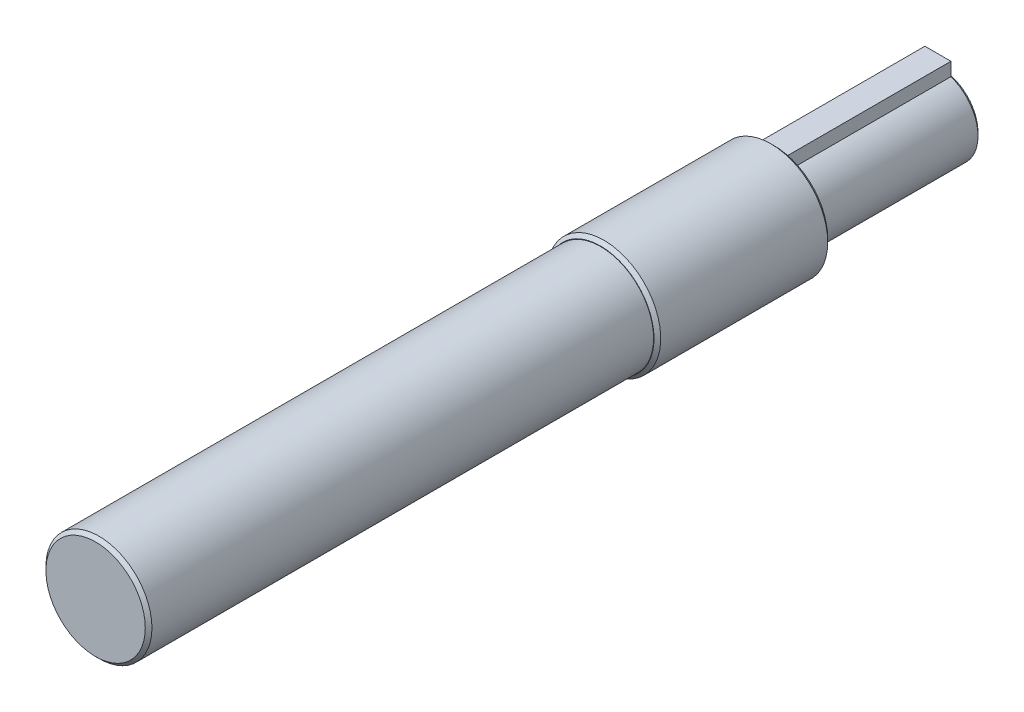
SolidWorks part; units mm, degrees
ref_plane "Front Plane" through (0, 0, 0) normal (0, 0, 1) x (1, 0, 0)
ref_plane "Top Plane" through (0, 0, 0) normal (0, 1, 0) x (1, 0, 0)
ref_plane "Right Plane" through (0, 0, 0) normal (1, 0, 0) x (0, 0, -1)
sketch "Sketch2" plane through (0, 0, 0) normal (0, 0, 1) x (1, 0, 0)
  circle A0 centre (0, 0) radius 6
  dimension "D1" = 12
extrude "Boss-Extrude1" add sketch "Sketch2" along normal blind 25.4
sketch "Sketch3" plane through (0, 0, 0) normal (0, 0, -1) x (-1, 0, 0)
  line L0 (-1.95, 5.6743) -> (-1.95, 7.6743)
  line L1 (-1.95, 7.6743) -> (1.95, 7.6743)
  line L2 (1.95, 7.6743) -> (1.95, 5.6743)
  circle A0 centre (0, 0) radius 6 construction
  arc A1 (-1.95, 5.6743) -> (1.95, 5.6743) centre (0, 0) ccw
  dimension "D1" = 3.9
  dimension "D2" = 1.95
  dimension "D3" = 2
extrude "Boss-Extrude2" add sketch "Sketch3" along normal blind 25
sketch "Sketch4" plane through (0, 0, 0) normal (0, 0, 1) x (1, 0, 0)
  circle A0 centre (0, 0) radius 8.5
  dimension "D1" = 17
extrude "Boss-Extrude3" add sketch "Sketch4" along normal blind 26
sketch "Sketch6" plane through (0, 0, 26) normal (0, 0, 1) x (1, 0, 0)
  circle A0 centre (0, 0) radius 7.9375
  dimension "D1" = 15.875
extrude "Boss-Extrude4" add sketch "Sketch6" along normal blind 75.6
chamfer "Chamfer1" distance 0.5 angle 45 7 edges at (7.9375, 0, 101.6) (1.95, 6.6743, -25) (0, 7.6743, -25) (-1.95, 6.6743, -25) (0, -6, -25) (8.5, 0, 26) (8.5, 0, 0)
